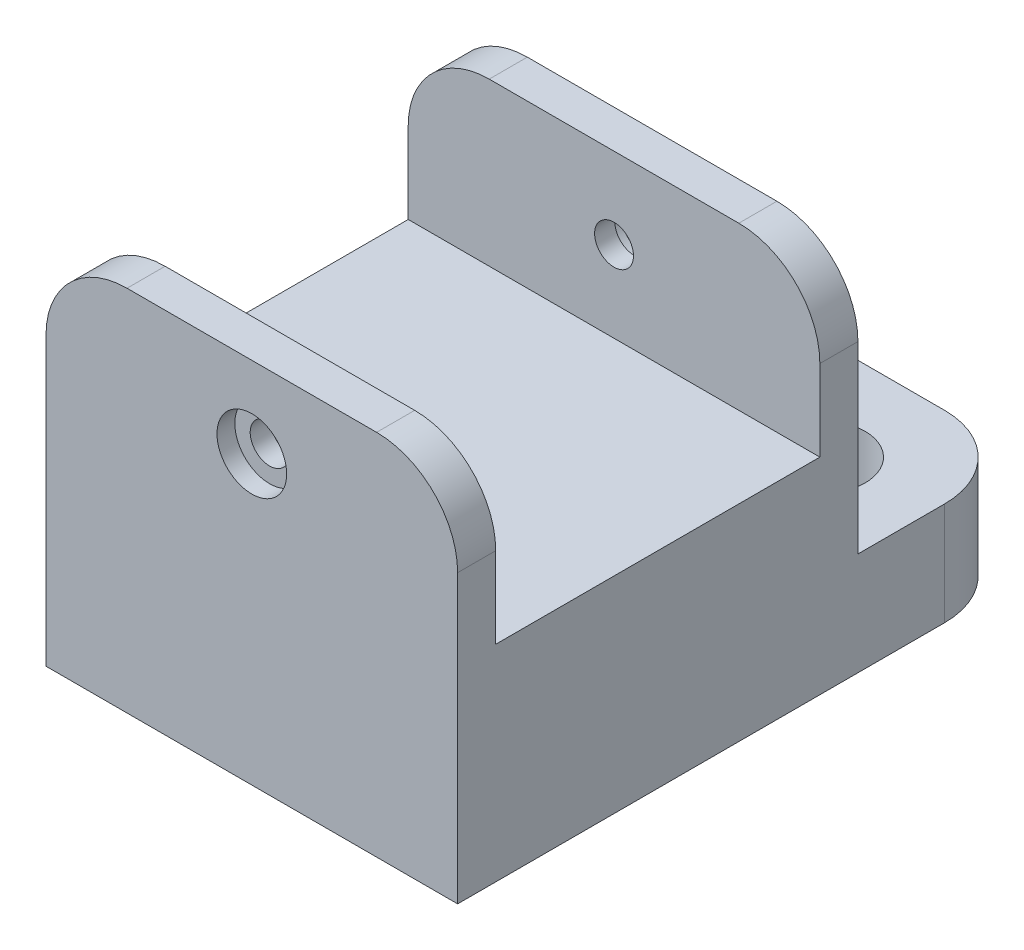
SolidWorks part; units mm, degrees
ref_plane "Front Plane" through (0, 0, 0) normal (0, 0, 1) x (1, 0, 0)
ref_plane "Top Plane" through (0, 0, 0) normal (0, 1, 0) x (1, 0, 0)
ref_plane "Right Plane" through (0, 0, 0) normal (1, 0, 0) x (0, 0, -1)
sketch "Sketch1" plane through (0, 0, 0) normal (0, 1, 0) x (1, 0, 0)
  line L1 (-23.0844, 20.5907) -> (27.7156, 20.5907)
  line L2 (-23.0844, 20.5907) -> (-23.0844, -4.8093)
  line L3 (-23.0844, -4.8093) -> (27.7156, -4.8093)
  line L4 (27.7156, 20.5907) -> (27.7156, -4.8093)
  dimension "D1" = 50.8
  dimension "D2" = 25.4
extrude "Boss-Extrude1" add sketch "Sketch1" along normal blind 25.4
sketch "Sketch2" plane through (0, 25.4, 0) normal (0, 1, 0) x (1, 0, 0)
  line L0 (27.7156, 20.5907) -> (-23.0844, 20.5907) construction
  line L1 (-10.3844, 20.5907) -> (15.0156, 20.5907)
  line L2 (-10.3844, 20.5907) -> (-10.3844, 7.8907)
  line L3 (-10.3844, 7.8907) -> (15.0156, 7.8907)
  line L4 (15.0156, 20.5907) -> (15.0156, 7.8907)
  line L5 (27.7156, -4.8093) -> (27.7156, 20.5907) construction
  line L6 (-23.0844, -4.8093) -> (27.7156, -4.8093) construction
  dimension "D1" = 12.7
  dimension "D2" = 25.4
  dimension "D3" = 12.7
hole_wizard "CBORE for 1/4 Socket Head Cap Screw1" positions "Sketch3" profile "Sketch5" counterbore size "1/4" standard "ANSI Inch" end condition through all
sketch "Sketch3" plane through (0, 25.4, 0) normal (0, 1, 0) x (1, 0, 0)
  point P0 (-10.3844, 7.8907)
  point P3 (15.0156, 7.8907)
sketch "Sketch5" plane through (-10.3844, 25.4, -7.8907) normal (1, 0, 0) x (0, 0, 1)
  line L0 (0, 0) -> (0, 25.4)
  line L1 (0, 25.4) -> (3.3782, 25.4)
  line L3 (3.3782, 25.4) -> (3.3782, 19.05)
  line L4 (3.3782, 19.05) -> (5.5562, 19.05)
  line L5 (5.5562, 19.05) -> (5.5563, 0)
  line L7 (5.5563, 0) -> (0, 0)
  line L11 (0, -6.35) -> (0, 107.95) construction
  dimension "Thru Hole Dia." = 6.7564
  dimension "Thru Hole Depth" = 25.4
  dimension "C'Bore Dia." = 11.1125
  dimension "C'Bore Depth" = 19.05
sketch "Sketch6" plane through (0, 25.4, 0) normal (0, 1, 0) x (1, 0, 0)
  line L0 (-23.0844, 20.5907) -> (-23.0844, -4.8093) construction
  line L1 (27.7156, 20.5907) -> (-23.0844, 20.5907)
  line L2 (27.7156, 20.5907) -> (27.7156, 15.8907)
  line L3 (27.7156, 15.8907) -> (-23.0844, 15.8907)
  line L4 (-23.0844, 20.5907) -> (-23.0844, 15.8907)
  circle A0 centre (15.0156, 7.8907) radius 5.5562 construction
  dimension "D1" = 8
extrude "Boss-Extrude2" add sketch "Sketch6" along normal blind 20
sketch "Sketch7" plane through (0, 0, -15.8907) normal (0, 0, 1) x (1, 0, 0)
  line L0 (-23.0844, 45.4) -> (27.7156, 45.4) construction
  line L1 (-10.3844, 45.4) -> (15.0156, 45.4)
  line L2 (-10.3844, 45.4) -> (-10.3844, 35.4)
  line L3 (-10.3844, 35.4) -> (15.0156, 35.4)
  line L4 (15.0156, 45.4) -> (15.0156, 35.4)
  line L5 (27.7156, 45.4) -> (27.7156, 25.4) construction
  line L7 (2.3156, 35.4) -> (2.3156, 45.4)
  dimension "D1" = 12.7
  dimension "D2" = 25.4
  dimension "D3" = 10
hole_wizard "CBORE for M4 SBHCS1" positions "Sketch12" profile "Sketch13" counterbore size "M4" standard "ANSI Metric" end condition through all
sketch "Sketch12" plane through (0, 0, -15.8907) normal (0, 0, 1) x (1, 0, 0)
  point P0 (2.3156, 35.4)
sketch "Sketch13" plane through (2.3156, 35.4, -15.8907) normal (1, 0, 0) x (0, -1, 0)
  line L0 (0, 0) -> (0, 4.7)
  line L1 (0, 4.7) -> (2.4, 4.7)
  line L3 (2.4, 4.7) -> (2.4, 2.2)
  line L4 (2.4, 2.2) -> (4.3, 2.2)
  line L5 (4.3, 2.2) -> (4.3, 0)
  line L7 (4.3, 0) -> (0, 0)
  line L11 (0, -6.35) -> (0, 107.95) construction
  dimension "Thru Hole Dia." = 4.8
  dimension "Thru Hole Depth" = 4.7
  dimension "C'Bore Dia." = 8.6
  dimension "C'Bore Depth" = 2.2
sketch "Sketch14" plane through (0, 0, -15.8907) normal (0, 0, 1) x (1, 0, 0)
  circle A0 centre (2.3156, 35.4) radius 5.295
fillet "Fillet1" radius 10 4 edges at (-23.0844, 45.4, -18.2407) (27.7156, 45.4, -18.2407) (27.7156, 12.7, 4.8093) (-23.0844, 12.7, 4.8093)
sketch "Sketch15" plane through (0, 0, -20.5907) normal (0, 0, -1) x (-1, 0, 0)
  line L0 (-27.7156, 35.4) -> (-27.7156, 0) construction
  line L1 (23.0844, 0) -> (-27.7156, 0)
  line L2 (23.0844, 0) -> (23.0844, 25.4)
  line L3 (23.0844, 25.4) -> (-27.7156, 25.4)
  line L4 (-27.7156, 0) -> (-27.7156, 25.4)
  dimension "D1" = 25.4
extrude "Boss-Extrude3" add sketch "Sketch15" along normal blind 20
sketch "Sketch16" plane through (0, 25.4, 0) normal (0, 1, 0) x (1, 0, 0)
  line L1 (-23.0844, 15.8907) -> (28.0289, 15.8907)
  line L2 (-23.0844, 15.8907) -> (-23.0844, -12.1026)
  line L3 (-23.0844, -12.1026) -> (28.0289, -12.1026)
  line L4 (28.0289, 15.8907) -> (28.0289, -12.1026)
extrude "Cut-Extrude2" cut sketch "Sketch16" against normal blind 12.7
mirror "Mirror1" about plane through (0, 0, -40.5907) normal (0, 0, -1) of bodies 109 107
sketch "Sketch17" plane through (0, 0, 4.8093) normal (0, 0, 1) x (1, 0, 0)
  line L1 (-23.0844, 12.7) -> (27.7156, 12.7)
  line L2 (-23.0844, 12.7) -> (-23.0844, 0)
  line L3 (-23.0844, 0) -> (27.7156, 0)
  line L4 (27.7156, 12.7) -> (27.7156, 0)
extrude "Cut-Extrude3" cut sketch "Sketch17" against normal up to surface (20.7 mm away) up to face at (6.6156, 35.4, -15.8907)
sketch "Sketch18" plane through (0, 25.4, 0) normal (0, 1, 0) x (1, 0, 0)
  circle A0 centre (-11.0283, 47.8907) radius 4.3567
  circle A1 centre (-10.3844, 73.2907) radius 3.3782 construction
  circle A2 centre (14.3717, 47.8907) radius 4.3794
  dimension "D2" = 25.4
  dimension "D1" = 25.4
